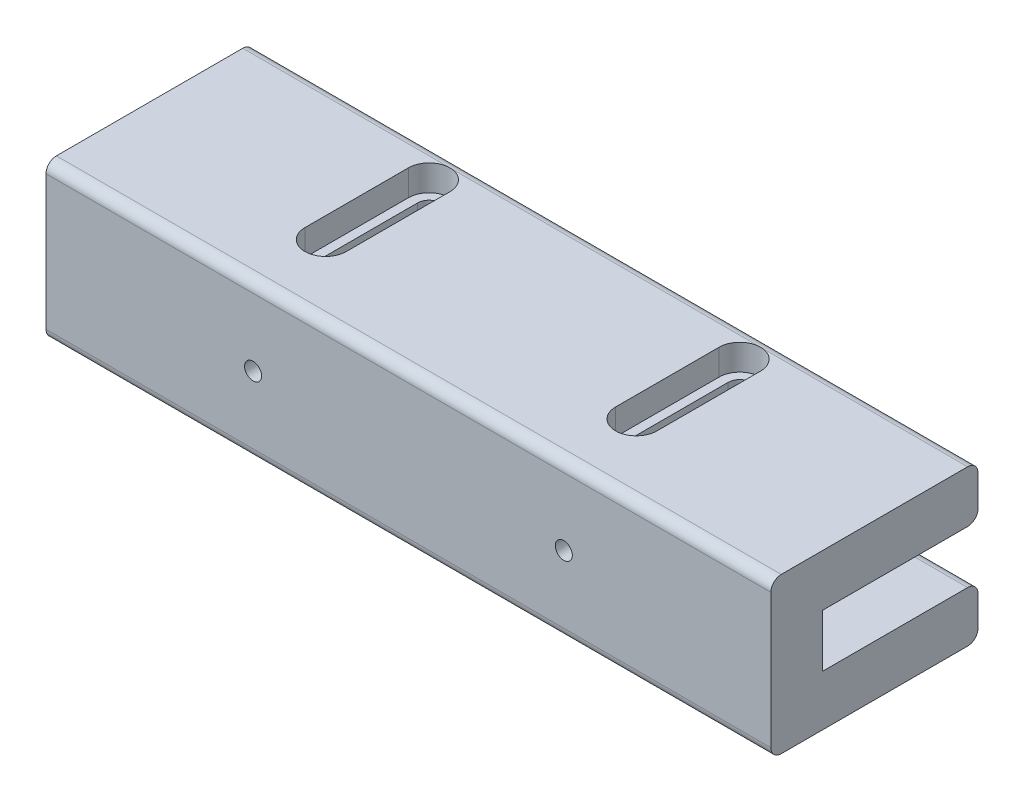
SolidWorks part; units mm, degrees
material "Alliage 1060"
ref_plane "Face" through (0, 0, 0) normal (0, 0, 1) x (1, 0, 0)
ref_plane "Dessus" through (0, 0, 0) normal (0, 1, 0) x (1, 0, 0)
ref_plane "Droite" through (0, 0, 0) normal (1, 0, 0) x (0, 0, -1)
sketch "Esquisse1" plane through (0, 0, 0) normal (1, 0, 0) x (0, 0, -1)
  line L1 (0, -15) -> (-40, -15)
  line L2 (0, -15) -> (0, 15)
  line L3 (0, 15) -> (-40, 15)
  line L4 (-40, -15) -> (-40, 15)
  dimension "D1" = 15
  dimension "D2" = 30
  dimension "D3" = 40
extrude "Boss.-Extru.1" add sketch "Esquisse1" along normal mid plane 140
sketch "Esquisse2" plane through (0, 0, 0) normal (1, 0, 0) x (0, 0, -1)
  line L0 (0, -15) -> (0, 15) construction
  line L1 (0, 5) -> (-30, 5)
  line L2 (0, 5) -> (0, -5.2)
  line L3 (0, -5.2) -> (-30, -5.2)
  line L4 (-30, 5) -> (-30, -5.2)
  dimension "D1" = 30
  dimension "D2" = 5
  dimension "D3" = 10.2
extrude "Enlèv. mat.-Extru.1" cut sketch "Esquisse2" against normal mid plane 200
fillet "Congé1" radius 2 6 edges at (0, -15, 0) (0, -5.2, 0) (0, 5, 0) (0, 15, 0) (0, -15, 40) (0, 15, 40)
sketch "Esquisse5" plane through (0, 15, 0) normal (0, 1, 0) x (1, 0, 0)
  line L0 (-70, 0) -> (70, 0) construction
  line L1 (-32.25, -6) -> (-32.25, -26)
  line L2 (-27.75, -6) -> (-27.75, -26)
  line L3 (32.25, -6) -> (32.25, -26)
  line L4 (27.75, -6) -> (27.75, -26)
  arc A0 (-27.75, -6) -> (-32.25, -6) centre (-30, -6) ccw
  arc A1 (-32.25, -26) -> (-27.75, -26) centre (-30, -26) ccw
  arc A2 (32.25, -6) -> (27.75, -6) centre (30, -6) ccw
  arc A3 (27.75, -26) -> (32.25, -26) centre (30, -26) ccw
  point P2 (0, 0)
  dimension "D1" = 30
  dimension "D2" = 6
  dimension "D3" = 20
extrude "Enlèv. mat.-Extru.2" cut sketch "Esquisse5" against normal up to next
sketch "Esquisse6" plane through (0, 15, 0) normal (0, 1, 0) x (1, 0, 0)
  line L0 (-34, -6) -> (-34, -26)
  line L1 (-26, -6) -> (-26, -26)
  line L2 (26, -6) -> (26, -26)
  line L3 (34, -6) -> (34, -26)
  arc A0 (-26, -6) -> (-34, -6) centre (-30, -6) ccw
  arc A1 (-34, -26) -> (-26, -26) centre (-30, -26) ccw
  arc A2 (34, -6) -> (26, -6) centre (30, -6) ccw
  arc A3 (26, -26) -> (34, -26) centre (30, -26) ccw
extrude "Enlèv. mat.-Extru.3" cut sketch "Esquisse6" against normal blind 5
hole_wizard "Trou taraudé M41" positions "Esquisse8" profile "Esquisse7" tap size "M4" standard "Iso" end condition up to next
sketch "Esquisse8" plane through (0, 0, 40) normal (0, 0, 1) x (1, 0, 0)
  point P0 (-30, 0)
  point P2 (30, 0)
  dimension "D1" = 30
  dimension "D2" = 30
sketch "Esquisse7" plane through (-30, 0, 40) normal (1, 0, 0) x (0, -1, 0)
  line L0 (0, 0) -> (0, 10)
  line L1 (0, 10) -> (1.65, 10)
  line L2 (1.65, 10) -> (1.65, 0)
  line L5 (1.65, 0) -> (0, 0)
  line L11 (0, -6.35) -> (0, 107.95) construction
  dimension "Diamètre du trou pour taraudage jusqu'au prochain" = 3.3
  dimension "Profondeur du trou pour taraudage jusqu'au prochain" = 10
cosmetic thread "Filetage de perçage1" parameters "D2"=4
cosmetic thread "Filetage de perçage2" parameters "D2"=4
